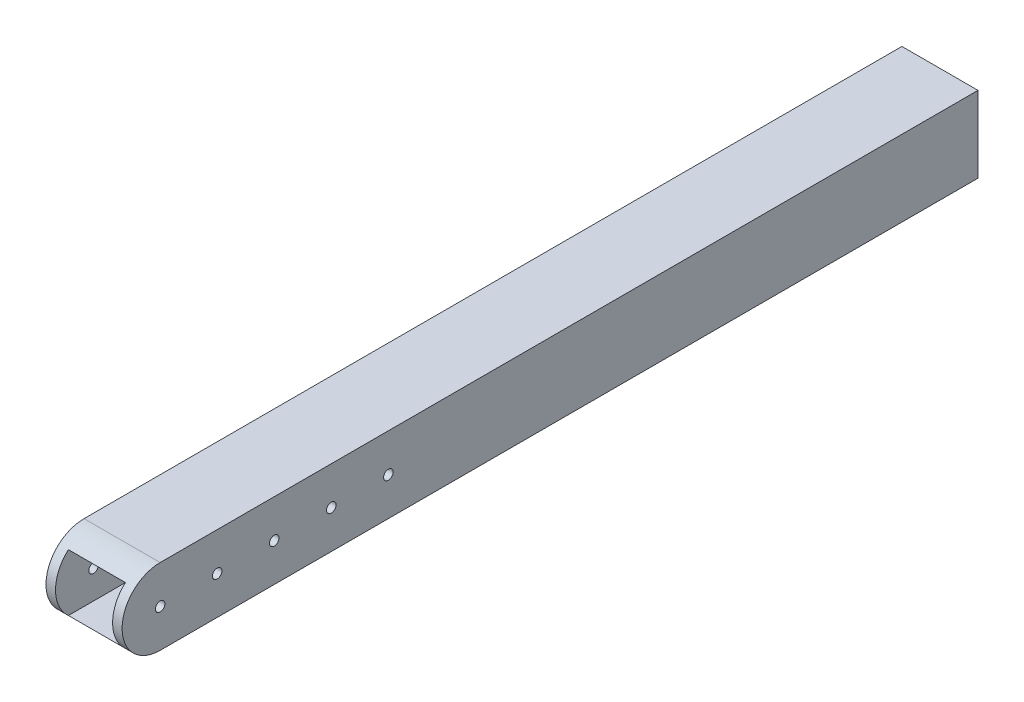
SolidWorks part; units mm, degrees
material "Plain Carbon Steel"
ref_plane "Front Plane" through (0, 0, 0) normal (0, 0, 1) x (1, 0, 0)
ref_plane "Top Plane" through (0, 0, 0) normal (0, 1, 0) x (1, 0, 0)
ref_plane "Right Plane" through (0, 0, 0) normal (1, 0, 0) x (0, 0, -1)
sketch "Sketch1" plane through (0, 0, 0) normal (0, 0, 1) x (1, 0, 0)
  line L0 (-15, 15) -> (15, 15)
  line L1 (-20, -20) -> (20, -20)
  line L2 (-20, -20) -> (-20, 20)
  line L3 (-20, 20) -> (20, 20)
  line L4 (20, -20) -> (20, 20)
  line L5 (-20, -20) -> (20, 20) construction
  line L6 (-20, 20) -> (20, -20) construction
  line L7 (15, -15) -> (15, 15)
  line L8 (-15, -15) -> (15, -15)
  line L9 (-15, -15) -> (-15, 15)
  point P0 (0, 0)
  dimension "D1" = 40
  dimension "D2" = 40
  dimension "D3" = 5
extrude "Boss-Extrude1" add sketch "Sketch1" along normal blind 450
sketch "Sketch2" plane through (20, 0, 0) normal (1, 0, 0) x (0, 0, -1)
  line L0 (-450, -20) -> (-450, 20) construction
  circle A0 centre (-430, 0) radius 2.5
  dimension "D1" = 5
  dimension "D2" = 20
extrude "Cut-Extrude1" cut sketch "Sketch2" against normal blind 450
sketch "Sketch3" plane through (20, 0, 0) normal (1, 0, 0) x (0, 0, -1)
  line L0 (-430, 20) -> (-450, 20)
  line L1 (-450, 20) -> (-450, -20)
  line L2 (-450, -20) -> (-430, -20)
  arc A0 (-430, 20) -> (-430, -20) centre (-430, 0) ccw
  line M4 (0, 20) -> (-450, 20)
  line M5 (-450, 20) -> (-450, -20)
  line M6 (-450, -20) -> (0, -20)
extrude "Cut-Extrude2" cut sketch "Sketch3" against normal blind 76 contours A0 M4 M5 | A0 L1 M6
pattern_linear "LPattern1" count 5 spacing 30 along (0, 0, -1) of "Cut-Extrude1"
